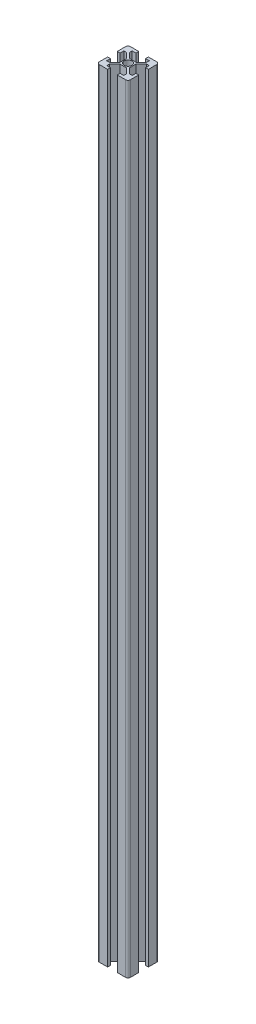
SolidWorks part; units mm, degrees
ref_plane "前视基准面" through (0, 0, 0) normal (0, 0, 1) x (1, 0, 0)
ref_plane "上视基准面" through (0, 0, 0) normal (0, 1, 0) x (1, 0, 0)
ref_plane "右视基准面" through (0, 0, 0) normal (1, 0, 0) x (0, 0, -1)
sketch "草图1" plane through (0, 0, 0) normal (0, 1, 0) x (1, 0, 0)
  line L0 (-13.5329, -11.5482) -> (-11.7329, -11.5482)
  line L1 (-12.0329, 1.5518) -> (4.9671, 1.5518)
  line L2 (-13.5329, 0.0518) -> (-13.5329, -16.9482)
  line L3 (-12.0329, -18.4482) -> (4.9671, -18.4482)
  line L4 (6.4671, 0.0518) -> (6.4671, -16.9482)
  line L5 (-13.5329, 1.5518) -> (6.4671, -18.4482) construction
  line L6 (-13.5329, -18.4482) -> (6.4671, 1.5518) construction
  line L7 (-6.587, -5.3482) -> (-0.4788, -5.3482)
  line L8 (-6.587, -5.3482) -> (-6.587, -11.5482)
  line L9 (-6.587, -11.5482) -> (-0.4788, -11.5482)
  line L10 (-0.4788, -5.3482) -> (-0.4788, -11.5482)
  line L11 (-6.587, -5.3482) -> (-0.4788, -11.5482) construction
  line L12 (-6.587, -11.5482) -> (-0.4788, -5.3482) construction
  line L13 (-11.7329, -11.5482) -> (-11.7329, -13.9482)
  line L14 (-11.7329, -13.9482) -> (-9.9299, -13.9482)
  line L15 (-9.9299, -13.9482) -> (-6.587, -10.6053)
  line L16 (-9.0329, -2.0512) -> (-5.69, -5.3941)
  line L17 (-9.0329, -0.2482) -> (-9.0329, -2.0512)
  line L18 (-6.6329, -0.2482) -> (-9.0329, -0.2482)
  line L19 (-6.6329, 1.5518) -> (-6.6329, -0.2482)
  line L20 (2.8642, -2.9482) -> (-0.4788, -6.2911)
  line L21 (4.6671, -2.9482) -> (2.8642, -2.9482)
  line L22 (4.6671, -5.3482) -> (4.6671, -2.9482)
  line L23 (6.4671, -5.3482) -> (4.6671, -5.3482)
  line L24 (1.9671, -14.8453) -> (-1.3758, -11.5024)
  line L25 (1.9671, -16.6482) -> (1.9671, -14.8453)
  line L26 (-0.4329, -16.6482) -> (1.9671, -16.6482)
  line L27 (-0.4329, -18.4482) -> (-0.4329, -16.6482)
  line L28 (-6.6329, -18.4482) -> (-6.6329, -16.6482)
  line L29 (-6.6329, -16.6482) -> (-9.0329, -16.6482)
  line L30 (-9.0329, -16.6482) -> (-9.0329, -14.8453)
  line L31 (-9.0329, -14.8453) -> (-5.69, -11.5024)
  line L32 (-11.7329, -2.9482) -> (-9.9299, -2.9482)
  line L33 (-9.9299, -2.9482) -> (-6.587, -6.2911)
  line L34 (-11.7329, -5.3482) -> (-11.7329, -2.9482)
  line L35 (-13.5329, -5.3482) -> (-11.7329, -5.3482)
  line L36 (1.9671, -0.2482) -> (1.9671, -2.0512)
  line L37 (1.9671, -2.0512) -> (-1.3758, -5.3941)
  line L38 (-0.4329, -0.2482) -> (1.9671, -0.2482)
  line L39 (-0.4329, 1.5518) -> (-0.4329, -0.2482)
  line L40 (4.6671, -13.9482) -> (2.8642, -13.9482)
  line L41 (2.8642, -13.9482) -> (-0.4788, -10.6053)
  line L42 (4.6671, -11.5482) -> (4.6671, -13.9482)
  line L43 (6.4671, -11.5482) -> (4.6671, -11.5482)
  circle A0 centre (-3.5329, -8.4482) radius 2.5
  arc A1 (-13.5329, 0.0518) -> (-12.0329, 1.5518) centre (-12.0329, 0.0518) cw
  arc A2 (-13.5329, -16.9482) -> (-12.0329, -18.4482) centre (-12.0329, -16.9482) ccw
  arc A3 (4.9671, 1.5518) -> (6.4671, 0.0518) centre (4.9671, 0.0518) cw
  arc A4 (6.4671, -16.9482) -> (4.9671, -18.4482) centre (4.9671, -16.9482) cw
  point P0 (-3.5329, -8.4482)
  point P19 (-3.5329, -8.4482)
  point P25 (-3.5329, -8.4482)
  point P31 (-3.5329, -8.4482)
  point P37 (-3.5329, -8.4482)
  point P59 (-3.5329, -8.4482)
extrude "凸台-拉伸1" add sketch "草图1" along normal blind 500.23
